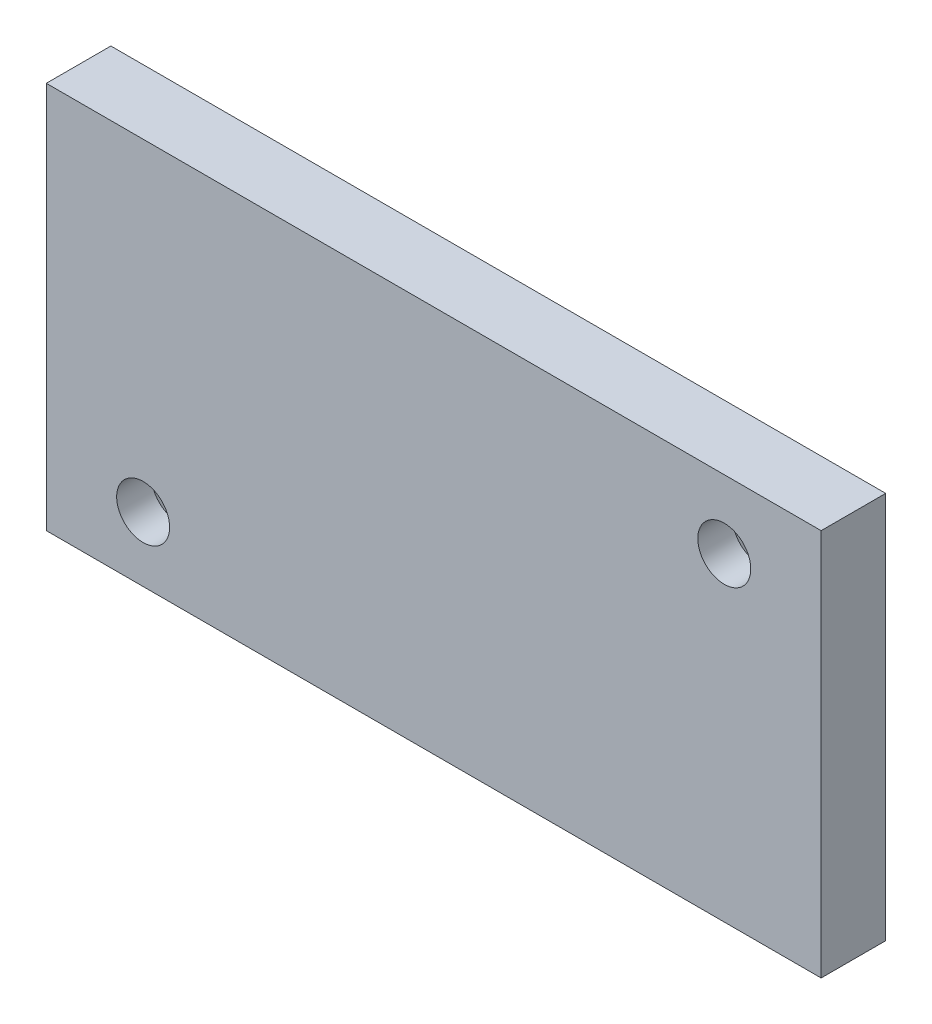
SolidWorks part; units mm, degrees
ref_plane "Front Plane" through (0, 0, 0) normal (0, 0, 1) x (1, 0, 0)
ref_plane "Top Plane" through (0, 0, 0) normal (0, 1, 0) x (1, 0, 0)
ref_plane "Right Plane" through (0, 0, 0) normal (1, 0, 0) x (0, 0, -1)
sketch "Sketch1" plane through (0, 0, 17.78) normal (0, 0, 1) x (1, 0, 0)
  line L0 (55, 0) -> (-55, 0) construction
  line L1 (-76.2, 0) -> (0, 0)
  line L2 (-76.2, 0) -> (-76.2, -38.1)
  line L3 (-76.2, -38.1) -> (0, -38.1)
  line L4 (0, 0) -> (0, -38.1)
  line L5 (0, -55) -> (0, 55) construction
  line L6 (-66.675, -31.75) -> (-66.675, -38.1) construction
  line L7 (-9.525, -6.731) -> (-9.525, 0) construction
  circle A2 centre (-9.525, -6.731) radius 2.6035
  circle A4 centre (-66.675, -31.75) radius 2.6035
  dimension "D1" = 5.207
  dimension "D4" = 6.731
  dimension "D6" = 5.207
  dimension "D2" = 76.2
  dimension "D3" = 38.1
  dimension "D5" = 6.35
extrude "Boss-Extrude1" add sketch "Sketch1" along normal blind 6.35
sketch "Sketch4" plane through (0, 0, 17.78) normal (0, 0, -1) x (-1, 0, 0)
  line L0 (76.2, -19.05) -> (0, -19.05) construction
  line L1 (76.2, 0) -> (76.2, -38.1) construction
  line L2 (0, 3.4925) -> (0, -3.4925) construction
  line L3 (0, -19.05) -> (0, -13.208)
  line L4 (0, -19.05) -> (0, -24.892)
  line L5 (76.2, -19.05) -> (76.2, -9.017)
  line L6 (76.2, -19.05) -> (76.2, -29.083)
  line L7 (0, -13.208) -> (76.2, -9.017)
  line L8 (0, -24.892) -> (76.2, -29.083)
  line L9 (0, -13.208) -> (0, 0)
  line L10 (0, 0) -> (76.2, 0)
  line L11 (3.4925, 0) -> (-3.4925, 0) construction
  line L12 (76.2, 0) -> (76.2, -9.017)
  line L13 (0, -13.208) -> (76.2, -9.017)
  line L14 (0, -24.892) -> (76.2, -29.083)
  line L15 (76.2, -38.1) -> (0, -38.1)
  line L16 (76.2, -38.1) -> (0, -38.1) construction
  line L17 (0, -38.1) -> (0, -24.892)
  dimension "D1" = 5.842
  dimension "D2" = 5.842
  dimension "D3" = 10.033
  dimension "D4" = 10.033
extrude "Cut-Extrude1" cut sketch "Sketch4" against normal blind 0.635
sketch "Sketch11" plane through (0, 0, 18.415) normal (0, 0, -1) x (-1, 0, 0)
  line L0 (0, 3.4925) -> (0, -3.4925) construction
  line L1 (0, -38.1) -> (5.08, -38.1)
  line L2 (0, -38.1) -> (0, -33.02)
  line L3 (0, -33.02) -> (5.08, -33.02)
  line L4 (5.08, -38.1) -> (5.08, -33.02)
  line L5 (0, -38.1) -> (76.2, -38.1) construction
  dimension "D1" = 5.08
  dimension "D2" = 5.08
  dimension "D3" = 0
sketch "Sketch13" plane through (0, 0, 18.415) normal (0, 0, -1) x (-1, 0, 0)
  line L1 (0, 0) -> (5.08, 0)
  line L2 (0, 0) -> (0, -5.08)
  line L3 (0, -5.08) -> (5.08, -5.08)
  line L4 (5.08, 0) -> (5.08, -5.08)
  dimension "D1" = 5.08
  dimension "D2" = 5.08
sketch "Sketch14" plane through (0, 0, 18.415) normal (0, 0, -1) x (-1, 0, 0)
  line L0 (2.54, -35.56) -> (73.66, -35.56)
  line L1 (73.66, -35.56) -> (73.66, -2.54)
  line L2 (73.66, -2.54) -> (2.54, -2.54)
  line L3 (2.54, -2.54) -> (2.54, -35.56)
  line L4 (0, 3.4925) -> (0, -3.4925) construction
  line L5 (3.4925, 0) -> (-3.4925, 0) construction
  line L6 (76.2, -9.017) -> (76.2, -29.083) construction
  line L7 (0, -38.1) -> (76.2, -38.1) construction
  line L8 (76.2, -38.1) -> (76.2, 0)
  line L9 (76.2, 0) -> (0, 0)
  line L10 (0, 0) -> (0, -38.1)
  line L11 (0, -38.1) -> (76.2, -38.1)
  dimension "D1" = 2.54
  dimension "D2" = 2.54
  dimension "D3" = 2.54
  dimension "D4" = 2.54
extrude "Boss-Extrude10" add sketch "Sketch14" along normal mid plane 1.27 contours L11 L8 L9 L10 | L3 L0 L1 L2
fillet "Fillet6" radius 3.175 8 edges at (-2.54, -35.56, 18.0975) (-2.54, -25.0317, 18.0975) (-73.66, -28.9433, 18.0975) (-73.66, -35.56, 18.0975) (-73.66, -9.1567, 18.0975) (-2.54, -13.0683, 18.0975) (-2.54, -2.54, 18.0975) (-73.66, -2.54, 18.0975)
sketch "Sketch17" plane through (0, 0, 18.415) normal (0, 0, -1) x (-1, 0, 0)
  line L0 (5.715, -2.54) -> (70.485, -2.54)
  line L1 (5.8894, -12.8841) -> (70.6594, -9.3217)
  line L2 (2.54, -9.7139) -> (2.54, -5.715)
  line L4 (73.66, -6.1515) -> (73.66, -5.715)
  arc A0 (73.66, -5.715) -> (70.485, -2.54) centre (70.485, -5.715) ccw
  arc A1 (2.54, -9.7139) -> (5.8894, -12.8841) centre (5.715, -9.7139) ccw
  arc A2 (2.54, -5.715) -> (5.715, -2.54) centre (5.715, -5.715) cw
  arc A3 (73.66, -6.1515) -> (70.6594, -9.3217) centre (70.485, -6.1515) cw
extrude "Cut-Extrude4" cut sketch "Sketch17" against normal blind 1.27
sketch "Sketch20" plane through (0, 0, 18.415) normal (0, 0, -1) x (-1, 0, 0)
  line L0 (5.8894, -25.2159) -> (70.6594, -28.7783)
  line L1 (70.485, -35.56) -> (5.715, -35.56)
  line L2 (2.54, -28.3861) -> (2.54, -32.385)
  line L3 (73.66, -31.9485) -> (73.66, -32.385)
  arc A0 (73.66, -32.385) -> (70.485, -35.56) centre (70.485, -32.385) cw
  arc A1 (70.6594, -28.7783) -> (73.66, -31.9485) centre (70.485, -31.9485) cw
  arc A2 (2.54, -28.3861) -> (5.8894, -25.2159) centre (5.715, -28.3861) cw
  arc A3 (2.54, -32.385) -> (5.715, -35.56) centre (5.715, -32.385) ccw
extrude "Cut-Extrude5" cut sketch "Sketch20" against normal blind 1.27
chamfer "Chamfer1" distance 1.016 angle 25 2 edges at (-64.0715, -31.75, 19.685) (-6.9215, -6.731, 19.685)
